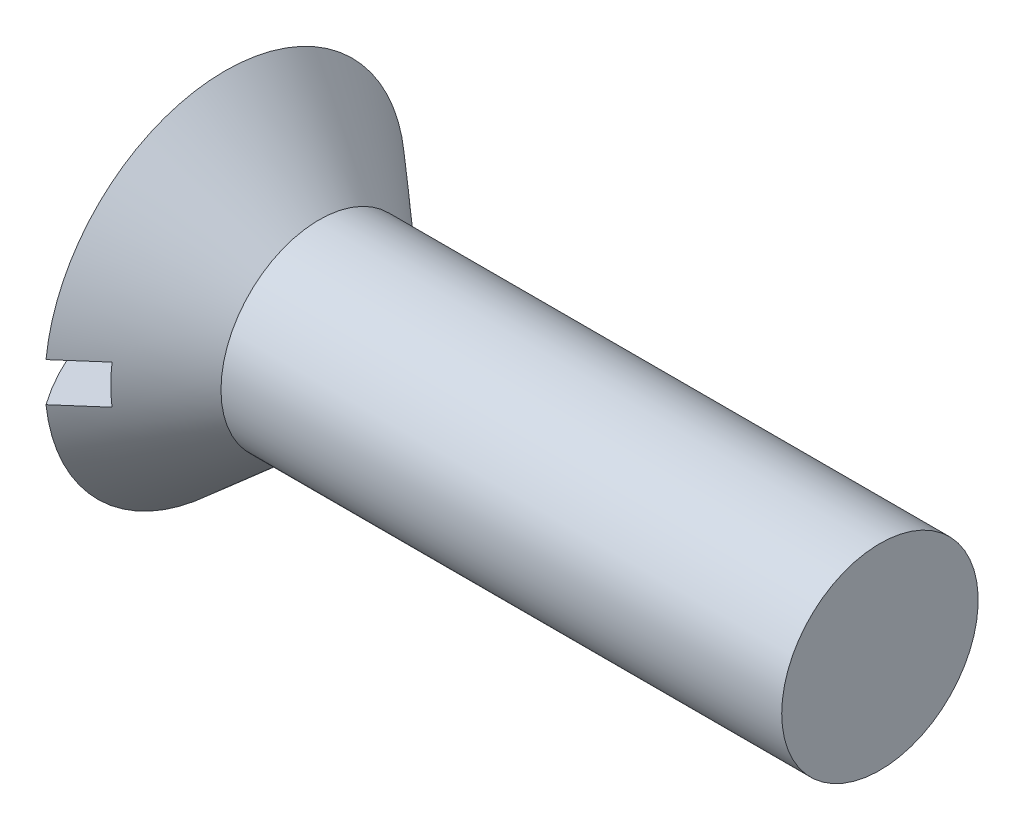
SolidWorks part; units mm, degrees
revolve "Base-Revolve" add sketch "BodySke" angle 360 about L4
sketch "BodySke" plane through (0, 0, 0) normal (0, 0, 1) x (1, 0, 0)
  line L0 (0, 0) -> (69.0502, 0)
  line L1 (69.0502, 0) -> (69.0502, 9.525)
  line L2 (69.0502, 9.525) -> (14.6812, 9.525)
  line L3 (5.5502, -17.4625) -> (14.6812, -9.525) construction
  line L4 (-15.875, 0) -> (82.55, 0) construction
  line L5 (5.5502, 17.4625) -> (14.6812, 9.525)
  line L6 (15.4749, 12.7) -> (15.475, -3.175) construction
  line L7 (37.3002, 12.7) -> (37.3002, -3.175) construction
  arc A0 (0, 0) -> (5.5502, 17.4625) centre (30.2463, 0) cw
  dimension "Head_ht" = 14.6812
  dimension "Head_ang" = 82
  dimension "Length" = 63.5
  dimension "Diameter" = 19.05
  dimension "Head_dia" = 34.925
  dimension "Advance" = 1.5875
  dimension "Thread_nom" = 31.75
cosmetic thread "ThreadCosmetic" [suppressed] parameters "Thread_length"=31.75, "Thread_minor"=16.0274
extrude "Slot" cut sketch "Sketch2" along normal blind 8.9662
sketch "Sketch2" plane through (0, 0, 0) normal (1, 0, 0) x (0, 0, -1)
  line L0 (17.4625, -1.8923) -> (-17.4625, -1.8923)
  line L1 (17.4625, -1.8923) -> (17.4625, 1.8923)
  line L2 (-17.4625, 1.8923) -> (17.4625, 1.8923)
  line L3 (-17.4625, 1.8923) -> (-17.4625, -1.8923)
  dimension "D1" = 34.925
  dimension "Slot_width" = 3.7846
  dimension "D3" = 17.4625
  dimension "D4" = 1.8923
ref_plane "Plane1" through (0, 0, 0) normal (0, 0, 1) x (1, 0, 0)
ref_plane "Plane2" through (0, 0, 0) normal (0, 1, 0) x (1, 0, 0)
ref_plane "Plane3" through (0, 0, 0) normal (1, 0, 0) x (0, 0, -1)
sketch "Sketch3" plane through (0, 0, 0) normal (1, 0, 0) x (0, 0, -1)
  line L0 (1.3208, -8.3312) -> (-1.3208, -8.3312)
  line L1 (1.3208, -8.3312) -> (1.3208, 8.3312)
  line L2 (-1.3208, 8.3312) -> (1.3208, 8.3312)
  line L3 (-1.3208, 8.3312) -> (-1.3208, -8.3312)
  dimension "Cross_width" = 2.6416
  dimension "D1" = 1.3208
  dimension "Cross_dia" = 16.6624
  dimension "D2" = 8.3312
ref_plane "Plane4" through (10.16, 0, 0) normal (1, 0, 0) x (0, 0, -1)
sketch "Sketch4" plane through (10.16, 0, 0) normal (1, 0, 0) x (0, 0, -1)
  line L0 (0.6604, -0.6604) -> (-0.6604, -0.6604)
  line L1 (0.6604, -0.6604) -> (0.6604, 0.6604)
  line L2 (-0.6604, 0.6604) -> (0.6604, 0.6604)
  line L3 (-0.6604, 0.6604) -> (-0.6604, -0.6604)
  dimension "D1" = 1.3208
  dimension "D2" = 1.3208
  dimension "D3" = 0.6604
  dimension "D4" = 0.6604
loft "Cross" cut profiles "Sketch3", "Sketch4"
pattern_circular "CirPattern1" count 2 every 90 about axis through (0, 0, 0) along (1, 0, 0) of "Cross"
sketch "ThdSchSke" plane through (0, 0, 0) normal (0, 0, 1) x (1, 0, 0)
  line L0 (37.3002, -8.0137) -> (36.242, -9.525)
  line L1 (37.3002, -8.0137) -> (38.3584, -9.525)
  line L2 (38.3584, -9.525) -> (38.3584, -11.9062)
  line L3 (-3.175, 0) -> (5.1513, 0) construction
  line L4 (5.5502, 17.4625) -> (5.5502, 1.8923) construction
  line L5 (38.3584, -11.9062) -> (36.242, -11.9063)
  line L6 (36.242, -11.9063) -> (36.242, -9.525)
  dimension "Diameter" = 19.05
  dimension "Thread_minor" = 16.0274
  dimension "Start" = 31.75
revolve "ThreadSchematic" [suppressed] cut sketch "ThdSchSke" angle 360 about L3
pattern_linear "ThdSchPat" [suppressed]
equation "\"D1@Sketch2\" = \"Head_dia@BodySke\""
equation "\"D3@Sketch2\" = \"D1@Sketch2\" / 2"
equation "\"D4@Sketch2\" = \"Slot_width@Sketch2\" / 2"
equation "\"D1@Sketch3\" = \"Cross_width@Sketch3\" / 2"
equation "\"D2@Sketch3\" = \"Cross_dia@Sketch3\" / 2"
equation "\"D1@Sketch4\" = \"Cross_width@Sketch3\"*.5"
equation "\"D2@Sketch4\" = \"D1@Sketch4\""
equation "\"D3@Sketch4\" = \"D1@Sketch4\" / 2"
equation "\"D4@Sketch4\" = \"D2@Sketch4\" / 2"
equation "\"Thread_length@ThreadCosmetic\" = ((sgn( (\"Length@BodySke\" - \"Advance@BodySke\" - ( ( ( \"Head_dia@BodySke\" - \"Diameter@BodySke\" ) * 0.5 ) / tan( \"Head_ang@BodySke\" * 0.008726646 ) ) ) - \"Thread_nom@BodySke\" )-1)*( (\"Length@BodySke\" - \"Advance@BodySke\" - ( ( ( \"Head_dia@BodySke\" - \"Diameter@BodySke\" ) * 0.5 ) / tan( \"Head_ang@BodySke\" * 0.008726646 ) ) ) - \"Thread_nom@BodySke\" ))/-2+ \"Thread_nom@BodySke\""
equation "\"Thread_minor@ThdSchSke\" = \"Thread_minor@ThreadCosmetic\""
equation "\"Diameter@ThdSchSke\" = \"Diameter@BodySke\""
equation "\"Overcut@ThdSchSke\" = \"Diameter@BodySke\" * 1.25"
equation "\"Start@ThdSchSke\" = 0.000001 + \"Length@BodySke\" - \"Thread_length@ThreadCosmetic\"  '---Countersunk---"
equation "\"Num_threads@ThdSchPat\" = int( \"Thread_length@ThreadCosmetic\" / \"Advance@BodySke\" + 0.999 )  + 1"
equation "\"Advance@ThdSchPat\" = \"Thread_length@ThreadCosmetic\" /  (\"Num_threads@ThdSchPat\" - 1) 'relax it"
